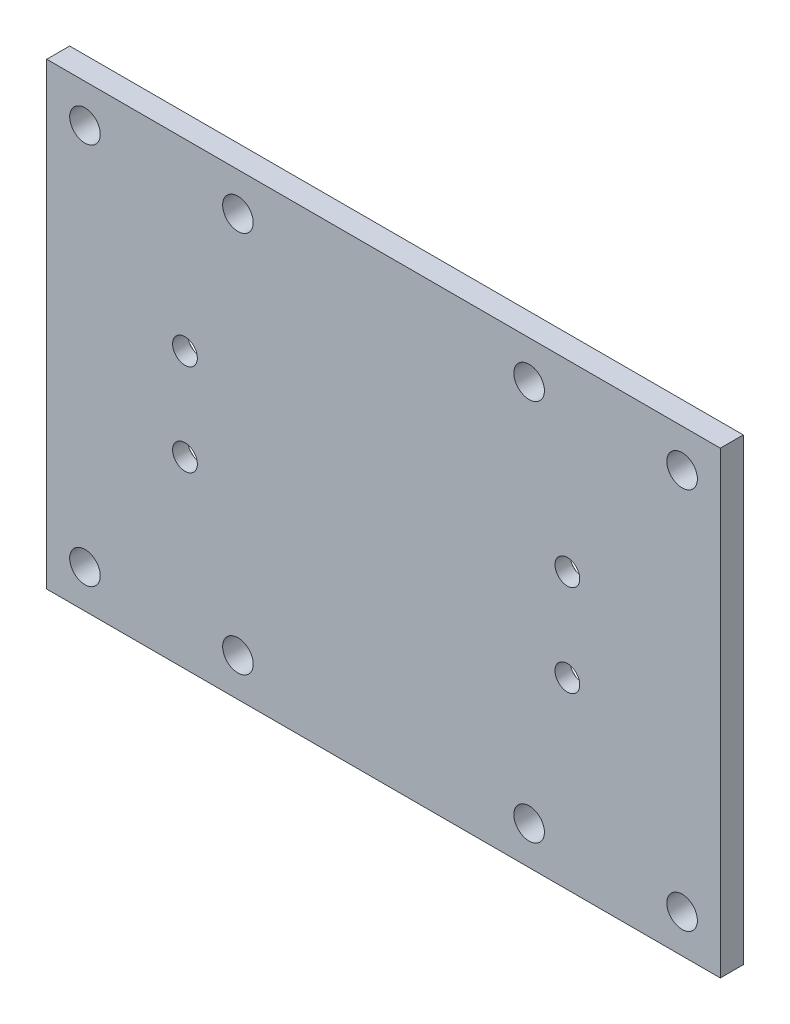
SolidWorks part; units mm, degrees
ref_plane "前视基准面" through (0, 0, 0) normal (0, 0, 1) x (1, 0, 0)
ref_plane "上视基准面" through (0, 0, 0) normal (0, 1, 0) x (1, 0, 0)
ref_plane "右视基准面" through (0, 0, 0) normal (1, 0, 0) x (0, 0, -1)
sketch "草图1" plane through (0, 0, 0) normal (0, 0, 1) x (1, 0, 0)
  line L1 (-164.4811, 60) -> (-76.4046, 60)
  line L2 (-164.4811, 60) -> (-164.4811, 0)
  line L3 (-164.4811, 0) -> (-76.4046, 0)
  line L4 (-76.4046, 60) -> (-76.4046, 0)
  dimension "D1" = 60
  dimension "D2" = 88.0764
extrude "凸台-拉伸1" add sketch "草图1" along normal blind 3
sketch "草图2" plane through (0, 0, 3) normal (0, 0, 1) x (1, 0, 0)
  line L0 (-164.4811, 0) -> (-76.4046, 0) construction
  line L1 (-164.4811, 60) -> (-164.4811, 0) construction
  line L2 (-76.4046, 60) -> (-164.4811, 60) construction
  line L3 (-76.4046, 0) -> (-76.4046, 60) construction
  circle A0 centre (-159.4811, 5) radius 2
  circle A1 centre (-159.4811, 55) radius 2
  circle A2 centre (-139.4811, 5) radius 2
  circle A3 centre (-139.4811, 55) radius 2
  circle A4 centre (-81.4046, 5) radius 2
  circle A5 centre (-81.4046, 55) radius 2
  circle A6 centre (-101.4046, 55) radius 2
  circle A7 centre (-101.4046, 5) radius 2
  dimension "D1" = 5
  dimension "D2" = 5
  dimension "D3" = 5
  dimension "D4" = 20
  dimension "D5" = 5
  dimension "D6" = 5
  dimension "D7" = 20
extrude "切除-拉伸1" cut sketch "草图2" against normal blind 3
sketch "草图3" plane through (0, 0, 0) normal (0, 0, -1) x (-1, 0, 0)
  line L0 (76.4046, 0) -> (76.4046, 60) construction
  line L1 (76.4046, 60) -> (164.4811, 60) construction
  line L2 (164.4811, 0) -> (76.4046, 0) construction
  circle A0 centre (96.4046, 36) radius 1.62
  circle A1 centre (96.4046, 24) radius 1.62
  circle A2 centre (146.4046, 36) radius 1.62
  circle A3 centre (146.4046, 24) radius 1.62
  dimension "D1" = 3.24
  dimension "D2" = 20
  dimension "D3" = 3.24
  dimension "D4" = 20
  dimension "D5" = 3.24
  dimension "D6" = 50
  dimension "D7" = 24
  dimension "D8" = 24
  dimension "D9" = 3.24
extrude "切除-拉伸2" cut sketch "草图3" against normal blind 3
sketch "草图4" plane through (0, 0, 0) normal (0, 0, -1) x (-1, 0, 0)
  circle A0 centre (96.4046, 36) radius 3
  circle A1 centre (96.4046, 24) radius 3
  circle A2 centre (146.4046, 36) radius 3
  circle A3 centre (146.4046, 24) radius 3
extrude "切除-拉伸3" cut sketch "草图4" against normal blind 1
